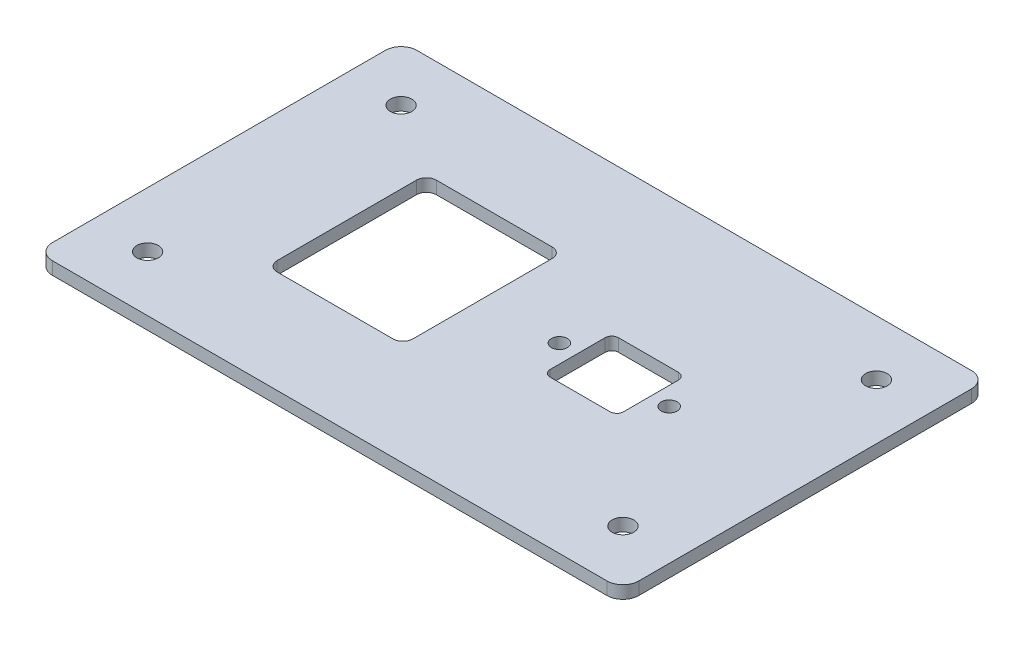
SolidWorks part; units mm, degrees
ref_plane "Front Plane" through (0, 0, 0) normal (0, 0, 1) x (1, 0, 0)
ref_plane "Top Plane" through (0, 0, 0) normal (0, 1, 0) x (1, 0, 0)
ref_plane "Right Plane" through (0, 0, 0) normal (1, 0, 0) x (0, 0, -1)
sketch "Sketch2" plane through (0, 0, 0) normal (0, 1, 0) x (1, 0, 0)
  line L0 (-33.1, 0) -> (33.1, 0) construction
  line L1 (14.5, -6.85) -> (26.5, -6.85)
  line L2 (13.15, -5.5) -> (13.15, 5.5)
  line L3 (14.5, 6.85) -> (26.5, 6.85)
  line L4 (27.85, -5.5) -> (27.85, 5.5)
  line L5 (13.15, -6.85) -> (27.85, 6.85) construction
  line L6 (13.15, 6.85) -> (27.85, -6.85) construction
  line L7 (-7.9, 15.95) -> (-31.1, 15.95)
  line L8 (-5.9, 13.95) -> (-5.9, -13.95)
  line L9 (-7.9, -15.95) -> (-31.1, -15.95)
  line L10 (-33.1, 13.95) -> (-33.1, -13.95)
  line L11 (-5.9, 15.95) -> (-33.1, -15.95) construction
  line L12 (-5.9, -15.95) -> (-33.1, 15.95) construction
  line L13 (-55.5625, -36.5125) -> (55.5625, -36.5125)
  line L14 (-58.7375, -33.3375) -> (-58.7375, 33.3375)
  line L15 (-55.5625, 36.5125) -> (55.5625, 36.5125)
  line L16 (58.7375, -33.3375) -> (58.7375, 33.3375)
  line L17 (-58.7375, -36.5125) -> (58.7375, 36.5125) construction
  line L18 (-58.7375, 36.5125) -> (58.7375, -36.5125) construction
  line L19 (0, 22.225) -> (0, -22.225) construction
  line L20 (-44.45, -22.225) -> (44.45, -22.225) construction
  line L21 (-44.45, -22.225) -> (-44.45, 22.225) construction
  line L22 (-44.45, 22.225) -> (44.45, 22.225) construction
  line L23 (44.45, -22.225) -> (44.45, 22.225) construction
  line L24 (-44.45, -22.225) -> (44.45, 22.225) construction
  line L25 (-44.45, 22.225) -> (44.45, -22.225) construction
  arc A0 (26.5, 6.85) -> (27.85, 5.5) centre (26.5, 5.5) cw
  arc A1 (13.15, 5.5) -> (14.5, 6.85) centre (14.5, 5.5) cw
  arc A2 (26.5, -6.85) -> (27.85, -5.5) centre (26.5, -5.5) ccw
  arc A3 (14.5, -6.85) -> (13.15, -5.5) centre (14.5, -5.5) cw
  circle A4 centre (9.5, 0) radius 1.6
  circle A5 centre (31.5, 0) radius 1.6
  arc A6 (-33.1, -13.95) -> (-31.1, -15.95) centre (-31.1, -13.95) ccw
  arc A7 (-7.9, -15.95) -> (-5.9, -13.95) centre (-7.9, -13.95) ccw
  arc A8 (-5.9, 13.95) -> (-7.9, 15.95) centre (-7.9, 13.95) ccw
  arc A9 (-31.1, 15.95) -> (-33.1, 13.95) centre (-31.1, 13.95) ccw
  circle A10 centre (47.625, 25.4) radius 2.1527
  circle A11 centre (47.625, -25.4) radius 2.1527
  circle A12 centre (-47.625, 25.4) radius 2.1527
  circle A13 centre (-47.625, -25.4) radius 2.1527
  arc A14 (55.5625, 36.5125) -> (58.7375, 33.3375) centre (55.5625, 33.3375) cw
  arc A15 (58.7375, -33.3375) -> (55.5625, -36.5125) centre (55.5625, -33.3375) cw
  arc A16 (-55.5625, -36.5125) -> (-58.7375, -33.3375) centre (-55.5625, -33.3375) cw
  arc A17 (-55.5625, 36.5125) -> (-58.7375, 33.3375) centre (-55.5625, 33.3375) ccw
  point P0 (20.5, 0)
  point P21 (0, 0)
  point P22 (-19.5, 0)
  point P41 (0, 0)
  point P46 (0, 0)
  dimension "D3" = 1.35
  dimension "D4" = 1.35
  dimension "D5" = 1.35
  dimension "D6" = 11
  dimension "D8" = 3.2
  dimension "D9" = 3.2
  dimension "D12" = 2
  dimension "D20" = 4.3053
  dimension "D21" = 3.175
  dimension "D1" = 13.7
  dimension "D2" = 14.7
  dimension "D7" = 11
  dimension "D10" = 27.2
  dimension "D11" = 31.9
  dimension "D13" = 40
  dimension "D14" = 88.9
  dimension "D15" = 44.45
  dimension "D16" = 14.2875
  dimension "D17" = 14.2875
  dimension "D18" = 3.175
  dimension "D19" = 3.175
extrude "Boss-Extrude1" add sketch "Sketch2" along normal blind 2.54
